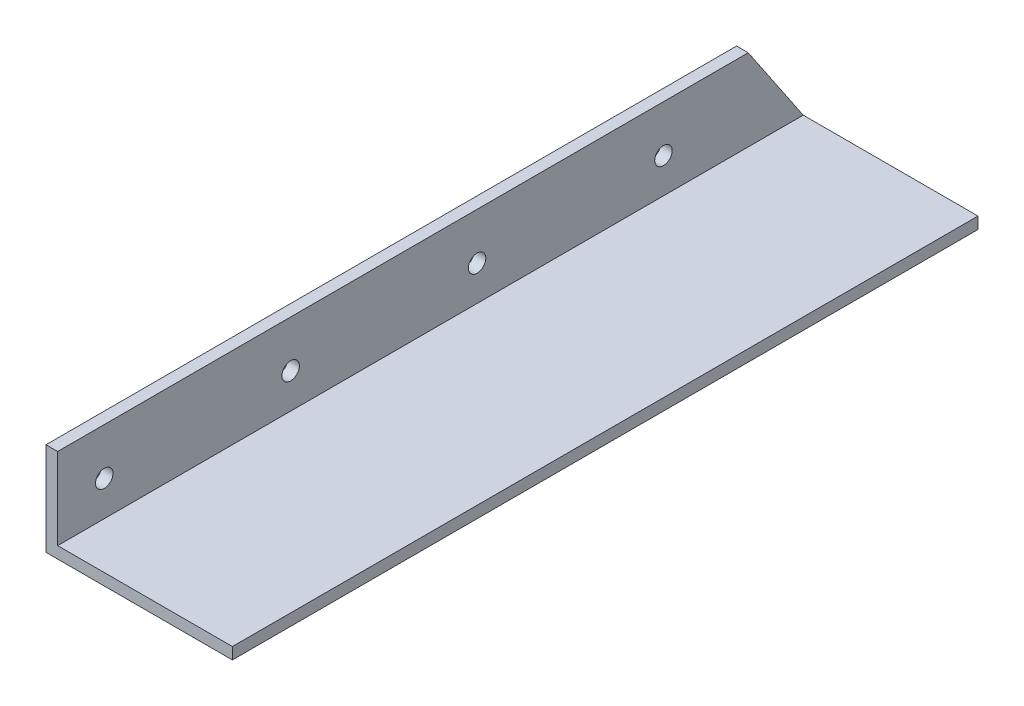
SolidWorks part; units mm, degrees
material "6063-T1"
ref_plane "Front Plane" through (0, 0, 0) normal (0, 0, 1) x (1, 0, 0)
ref_plane "Top Plane" through (0, 0, 0) normal (0, 1, 0) x (1, 0, 0)
ref_plane "Right Plane" through (0, 0, 0) normal (1, 0, 0) x (0, 0, -1)
sketch "Sketch1" plane through (0, 0, 0) normal (0, 0, 1) x (1, 0, 0)
  line L1 (0, 0) -> (50.8, 0)
  line L2 (0, 0) -> (0, 25.4)
  line L3 (0, 25.4) -> (50.8, 25.4)
  line L4 (50.8, 0) -> (50.8, 25.4)
  line L5 (50.8, 25.4) -> (3.175, 25.4)
  line L6 (50.8, 25.4) -> (50.8, 3.175)
  line L7 (50.8, 3.175) -> (3.175, 3.175)
  line L8 (3.175, 25.4) -> (3.175, 3.175)
  dimension "D1" = 3.175
  dimension "D2" = 3.175
  dimension "D3" = 25.4
  dimension "D4" = 50.8
extrude "Boss-Extrude1" add sketch "Sketch1" along normal blind 203.2 contours L8 L3 L2 L1 L4 L7
sketch "Sketch2" plane through (0, 0, 0) normal (-1, 0, 0) x (0, 0, 1)
  line L0 (203.2, 0) -> (0, 0) construction
  line L1 (203.2, 0) -> (203.2, 25.4) construction
  circle A0 centre (190.5, 12.7) radius 2.3813
  circle A1 centre (139.7, 12.7) radius 2.3813
  circle A2 centre (88.9, 12.7) radius 2.3813
  circle A3 centre (38.1, 12.7) radius 2.3813
  circle A4 centre (-12.7, 12.7) radius 2.3813
  dimension "D3" = 4.7625
  dimension "D1" = 12.7
  dimension "D2" = 12.7
  dimension "D4" = 5
extrude "Cut-Extrude1" cut sketch "Sketch2" against normal through all
chamfer "Chamfer1" [suppressed] distance 50.8 angle 45
chamfer "Chamfer2" [suppressed] distance 50.8 angle 45
chamfer "Chamfer4" distance 22.225 angle 34 1 edges at (1.5875, 25.4, 0)
